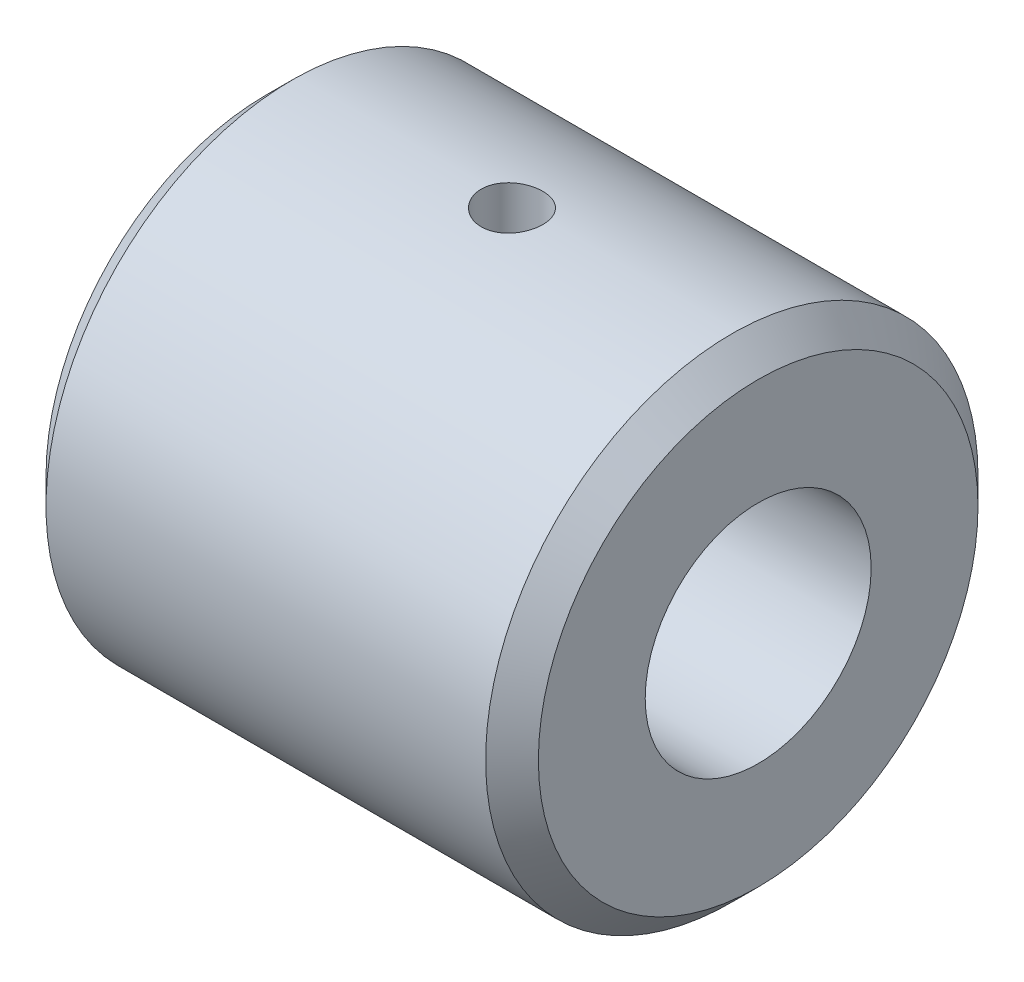
SolidWorks part; units mm, degrees
material "6061 Alloy"
ref_plane "Front Plane" through (0, 0, 0) normal (0, 0, 1) x (1, 0, 0)
ref_plane "Top Plane" through (0, 0, 0) normal (0, 1, 0) x (1, 0, 0)
ref_plane "Right Plane" through (0, 0, 0) normal (1, 0, 0) x (0, 0, -1)
sketch "Sketch1" plane through (0, 0, 0) normal (1, 0, 0) x (0, 0, -1)
  circle A0 centre (0, 0) radius 3.556
  dimension "D1" = 7.112
extrude "Boss-Extrude1" add sketch "Sketch1" along normal mid plane 7.112
hole_wizard "#30 (0.1285) Diameter Hole1" positions "Sketch2" profile "Sketch3" hole size "#30" standard "ANSI Inch" end condition through all
sketch "Sketch2" plane through (3.556, 0, 0) normal (1, 0, 0) x (0, 0, -1)
  point P0 (0, 0)
sketch "Sketch3" plane through (3.556, 0, 0) normal (0, 1, 0) x (0, 0, -1)
  line L0 (0, 0) -> (0, 7.112)
  line L1 (0, 7.112) -> (1.6319, 7.112)
  line L2 (1.6319, 7.112) -> (1.6319, 0)
  line L5 (1.6319, 0) -> (0, 0)
  line L11 (0, -6.35) -> (0, 107.95) construction
  dimension "Thru Hole Dia." = 3.2639
  dimension "Thru Hole Depth" = 7.112
chamfer "Chamfer2" distance 0.381 angle 45 2 edges at (-3.556, 0, -3.556) (3.556, 0, -3.556)
ref_plane "Plane1" through (0, 3.556, 0) normal (0, 1, 0) x (1, 0, 0)
hole_wizard "#65 (0.035) Diameter Hole2" positions "Sketch9" profile "Sketch10" hole size "#65" standard "ANSI Inch" end condition through all
sketch "Sketch9" plane through (0, 3.556, 0) normal (0, 1, 0) x (1, 0, 0)
  point P0 (0, 0)
sketch "Sketch10" plane through (0, 3.556, 0) normal (1, 0, 0) x (0, 0, 1)
  line L0 (0, 0) -> (0, 7.112)
  line L1 (0, 7.112) -> (0.4445, 7.112)
  line L2 (0.4445, 7.112) -> (0.4445, 0)
  line L5 (0.4445, 0) -> (0, 0)
  line L11 (0, -6.35) -> (0, 107.95) construction
  dimension "Thru Hole Dia." = 0.889
  dimension "Thru Hole Depth" = 7.112
